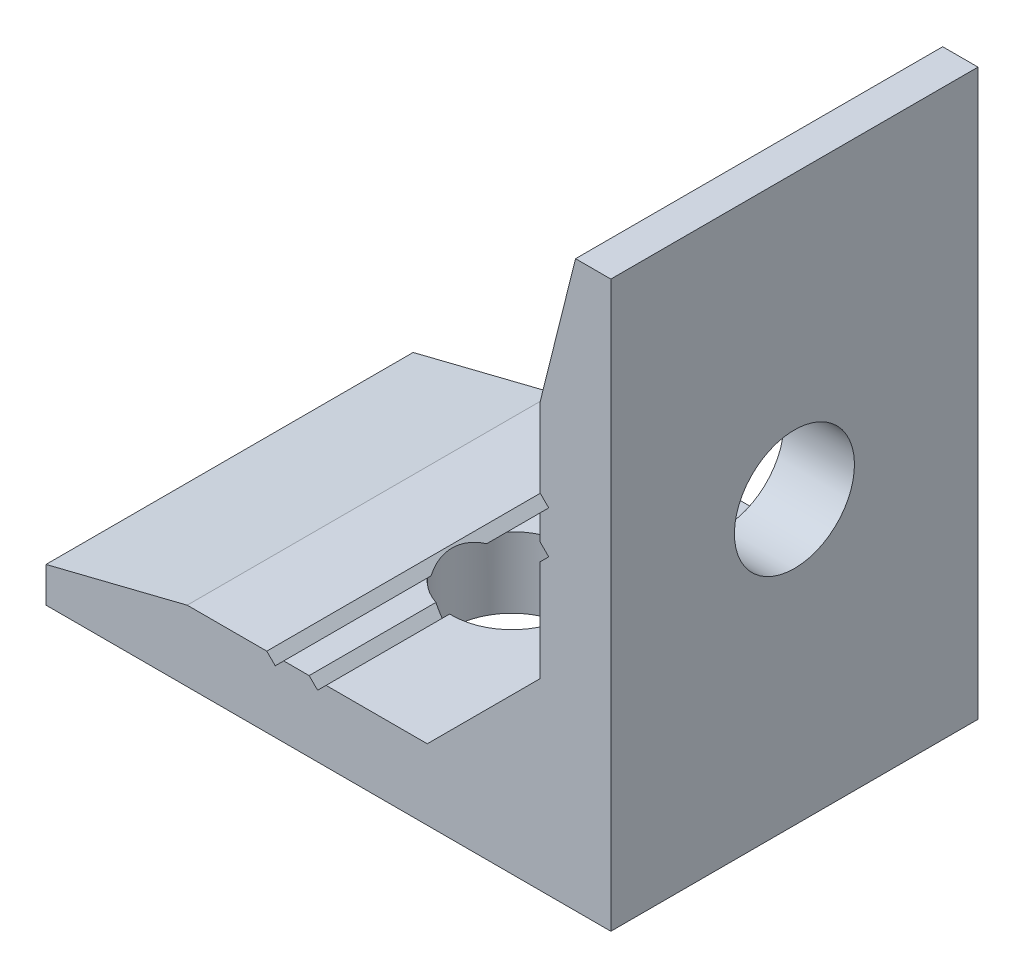
SolidWorks part; units mm, degrees
ref_plane "前视基准面" through (0, 0, 0) normal (0, 0, 1) x (1, 0, 0)
ref_plane "上视基准面" through (0, 0, 0) normal (0, 1, 0) x (1, 0, 0)
ref_plane "右视基准面" through (0, 0, 0) normal (1, 0, 0) x (0, 0, -1)
sketch "草图1" plane through (0, 0, 0) normal (0, 0, 1) x (1, 0, 0)
  line B0 (0, 0) -> (40, 0)
  line B1 (40, 0) -> (40, 40)
  line B2 (10, 5) -> (15.635, 5)
  line B3 (16.835, 5) -> (18.635, 5)
  line B4 (19.835, 5) -> (27, 5)
  line B5 (35, 13) -> (35, 20.165)
  line B6 (35, 21.365) -> (35, 23.165)
  line B7 (35, 24.365) -> (35, 30)
  line B8 (0, 2.5) -> (0, 0)
  line B9 (37.5, 40) -> (40, 40)
  line B10 (0, 2.5) -> (10, 5)
  line B11 (37.5, 40) -> (35, 30)
  line B12 (27, 5) -> (35, 13)
  line B13 (16.235, 4.4) -> (15.635, 5)
  line B14 (16.235, 4.4) -> (16.835, 5)
  line B15 (19.235, 4.4) -> (18.635, 5)
  line B16 (19.235, 4.4) -> (19.835, 5)
  line B17 (35.6, 23.765) -> (35, 24.365)
  line B18 (35.6, 23.765) -> (35, 23.165)
  line B19 (35.6, 20.765) -> (35, 21.365)
  line B20 (35.6, 20.765) -> (35, 20.165)
sketch_block_instance "A$C2EE5613F-1"
sketch_block "A$C2EE5613F"
extrude "凸台-拉伸1" add sketch "草图1" along normal mid plane 26
sketch "草图3" plane through (0, 5, 0) normal (0, 1, 0) x (1, 0, 0)
  line L0 (0, -13) -> (0, 13) construction
  circle A0 centre (20, 0) radius 4.25
  dimension "D1" = 20
extrude "切除-拉伸1" cut sketch "草图3" against normal through all
sketch "草图4" plane through (35, 0, 0) normal (-1, 0, 0) x (0, 0, 1)
  line L0 (13, 40) -> (-13, 40) construction
  circle A0 centre (0, 20) radius 4.25
  dimension "D1" = 20
extrude "切除-拉伸2" cut sketch "草图4" against normal through all
